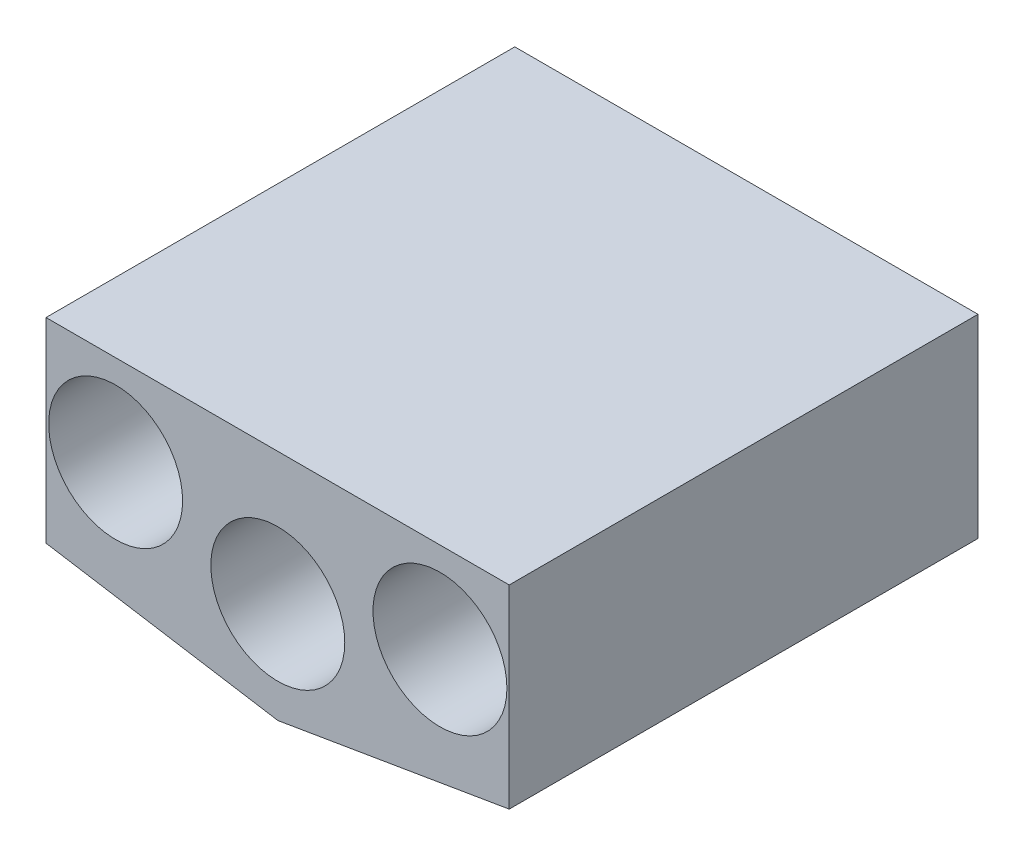
SolidWorks part; units mm, degrees
ref_plane "Ön Düzlem" through (0, 0, 0) normal (0, 0, 1) x (1, 0, 0)
ref_plane "Üst Düzlem" through (0, 0, 0) normal (0, 1, 0) x (1, 0, 0)
ref_plane "Sağ Düzlem" through (0, 0, 0) normal (1, 0, 0) x (0, 0, -1)
sketch "Çizim1" plane through (0, 0, 0) normal (0, 0, 1) x (1, 0, 0)
  line L0 (-47.2519, 0) -> (42.2089, 0) construction
  line L1 (0, -39.0014) -> (0, 37.2386) construction
  line L2 (0, 0) -> (24.2146, 6.2172) construction
  line L4 (0, 0) -> (-24.2146, 6.2172) construction
  line L6 (0, 0) -> (0, -10) construction
  line L19 (34.558, -9.2532) -> (0.0146, -15.0679)
  line L20 (-34.612, -9.4442) -> (0.0146, -15.0679)
  line L21 (-34.612, -9.4442) -> (-34.612, 19.7407)
  line L22 (-34.612, 19.7407) -> (34.558, 19.7407)
  line L23 (34.558, 19.7407) -> (34.558, -9.2532)
  circle A1 centre (-24.2146, 6.2172) radius 10
  circle A2 centre (0, 0) radius 10
  circle A3 centre (24.2146, 6.2172) radius 10
  dimension "D7" = 104.4
  dimension "D1" = 151.2
  dimension "D2" = 10
  dimension "D4" = 25
  dimension "D5" = 25
  dimension "D12" = 48.4292
extrude "Yükseklik-Ekstrüzyon2" add sketch "Çizim1" along normal blind 70
sketch "Çizim4" plane through (-2.3839, -14.6783, 0) normal (-0.1603, -0.9871, 0) x (0.9871, -0.1603, 0)
  line L0 (-32.6504, 70) -> (-10.6504, 70) construction
  line L1 (-32.6504, 70) -> (2.43, 70) construction
  line L2 (-32.6504, 0) -> (-10.6504, 0) construction
  line L3 (-32.6504, 0) -> (2.43, 0) construction
  line L4 (-10.6504, 70) -> (-10.6504, 60) construction
  line L5 (-10.6504, 0) -> (-10.6504, 10) construction
  circle A0 centre (-10.6504, 60) radius 2.9
  circle A1 centre (-10.6504, 10) radius 2.9
  dimension "D2" = 5.8
  dimension "D3" = 5.8
  dimension "D1" = 22
  dimension "D4" = 10
extrude "Kes-Ekstrüzyon1" cut sketch "Çizim4" along direction (0, 1, 0) on the side against the normal blind 10
sketch "Çizim6" plane through (2.4669, -14.6551, 0) normal (0.166, -0.9861, 0) x (0.9861, 0.166, 0)
  line L0 (32.5426, 0) -> (10.5426, 0) construction
  line L1 (-2.4868, 0) -> (32.5426, 0) construction
  line L2 (10.5426, 0) -> (10.5426, 10) construction
  line L3 (32.5426, 70) -> (10.5426, 70) construction
  line L4 (-2.4868, 70) -> (32.5426, 70) construction
  line L5 (10.5426, 70) -> (10.5426, 60) construction
  circle A0 centre (10.5426, 60) radius 2.9
  circle A1 centre (10.5426, 10) radius 2.9
extrude "Kes-Ekstrüzyon2" cut sketch "Çizim6" along direction (0, 1, 0) on the side against the normal blind 10
sketch "Çizim7" plane through (2.4669, -14.6551, 0) normal (0.166, -0.9861, 0) x (0.9861, 0.166, 0)
  line L0 (-2.4868, 70) -> (32.5426, 70) construction
  line L1 (10.5426, 60) -> (-2.4868, 60)
  line L2 (7.6426, 60) -> (-2.4868, 60) construction
  line L3 (-2.4868, 70) -> (-2.4868, 0) construction
  line L4 (10.5426, 60) -> (10.5426, 10) construction
  line L5 (10.5426, 60) -> (10.5426, 70)
  line L6 (10.5426, 10) -> (-2.4868, 10) construction
  line L7 (10.5426, 10) -> (10.5426, 0) construction
  line L8 (-2.4868, 0) -> (32.5426, 0) construction
  circle A1 centre (10.5426, 60) radius 2.9 construction
  dimension "D1" = 10
  dimension "D2" = 13.0294
  dimension "D3" = 50
  dimension "D4" = 10
